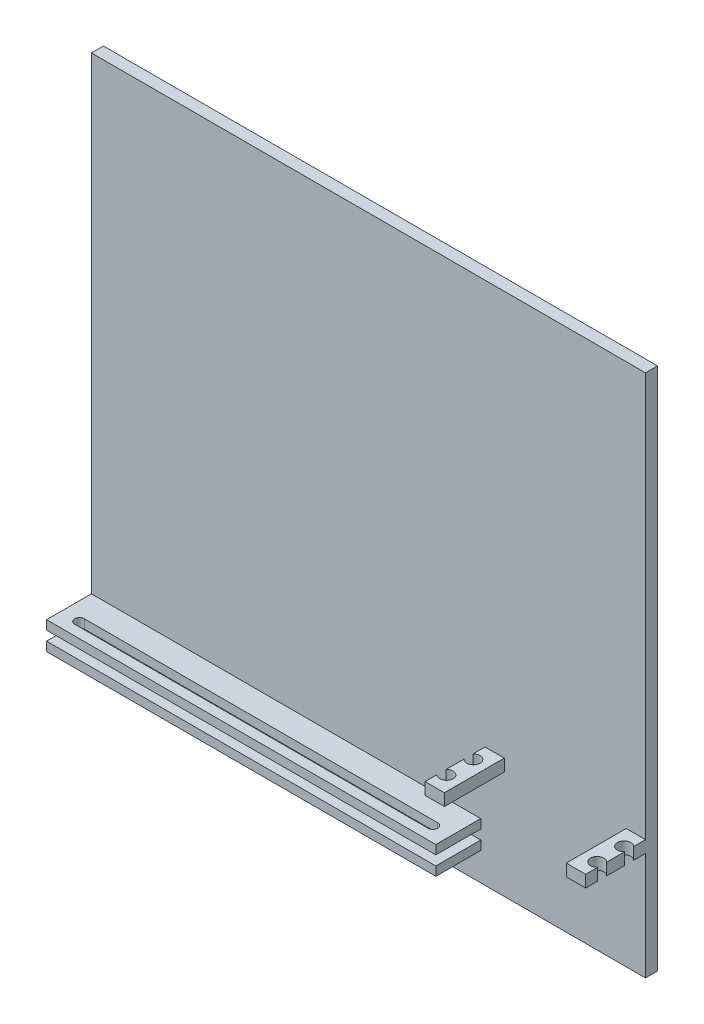
SolidWorks part; units mm, degrees
ref_plane "前基準面" through (0, 0, 0) normal (0, 0, 1) x (1, 0, 0)
ref_plane "上基準面" through (0, 0, 0) normal (0, 1, 0) x (1, 0, 0)
ref_plane "右基準面" through (0, 0, 0) normal (1, 0, 0) x (0, 0, -1)
sketch "草圖1" plane through (0, 0, 0) normal (0, 0, 1) x (1, 0, 0)
  line L1 (-102.146, 128.6132) -> (82.854, 128.6132)
  line L2 (-102.146, 128.6132) -> (-102.146, -46.3868)
  line L3 (-102.146, -46.3868) -> (82.854, -46.3868)
  line L4 (82.854, 128.6132) -> (82.854, -46.3868)
  dimension "D1" = 185
  dimension "D2" = 175
extrude "填料-伸長1" add sketch "草圖1" along normal blind 4
sketch "草圖2" plane through (0, 0, 4) normal (0, 0, 1) x (1, 0, 0)
  line L0 (76.204, -10.3868) -> (82.254, -10.3868) construction
  line L1 (76.404, -10.3868) -> (82.854, -10.3868)
  line L2 (76.404, -10.3868) -> (76.404, -6.3868)
  line L3 (76.404, -6.3868) -> (82.854, -6.3868)
  line L4 (82.854, -10.3868) -> (82.854, -6.3868)
  line L5 (76.204, 15.6132) -> (76.204, -10.3868) construction
  line L6 (82.854, -46.3868) -> (82.854, 128.6132) construction
  line L7 (29.854, -10.3868) -> (35.904, -10.3868) construction
  line L8 (35.704, -10.3868) -> (29.254, -10.3868)
  line L9 (35.704, -10.3868) -> (35.704, -6.3868)
  line L10 (35.704, -6.3868) -> (29.254, -6.3868)
  line L11 (29.254, -10.3868) -> (29.254, -6.3868)
  line L12 (35.904, -10.3868) -> (35.904, 15.6132) construction
  line L13 (29.254, -12.7868) -> (29.254, -10.9868) construction
  dimension "D1" = 0.2
  dimension "D2" = 4
  dimension "D3" = 0.2
  dimension "D4" = 4
extrude "填料-伸長2" add sketch "草圖2" along normal up to vertex (20 mm away)
sketch "草圖3" plane through (0, -10.3868, 0) normal (0, -1, 0) x (1, 0, 0)
  circle A0 centre (81.204, 18.5) radius 2.22
  circle A1 centre (81.204, 9.5) radius 2.22
  circle A2 centre (30.904, 9.5) radius 2.22
  circle A3 centre (30.904, 18.5) radius 2.22
extrude "除料-伸長1" cut sketch "草圖3" against normal up to next
sketch "草圖4" plane through (0, 0, 4) normal (0, 0, 1) x (1, 0, 0)
  line L0 (-102.146, 128.6132) -> (-102.146, -46.3868) construction
  line L1 (-102.146, -30.7868) -> (27.854, -30.7868)
  line L2 (-102.146, -30.7868) -> (-102.146, -27.7868)
  line L3 (-102.146, -27.7868) -> (27.854, -27.7868)
  line L4 (27.854, -30.7868) -> (27.854, -27.7868)
  line L5 (64.3284, -30.8868) -> (19.9992, -30.8868) construction
  line L6 (-102.146, -33.9868) -> (27.854, -33.9868)
  line L7 (-102.146, -33.9868) -> (-102.146, -36.9868)
  line L8 (-102.146, -36.9868) -> (27.854, -36.9868)
  line L9 (27.854, -33.9868) -> (27.854, -36.9868)
  dimension "D1" = 0.1
  dimension "D2" = 3
  dimension "D3" = 130
  dimension "D4" = 3.2
  dimension "D5" = 130
  dimension "D6" = 3
extrude "填料-伸長3" add sketch "草圖4" along normal blind 15
sketch "草圖5" plane through (0, -36.9868, 0) normal (0, -1, 0) x (1, 0, 0)
  line L0 (-96.146, 14) -> (21.854, 14) construction
  line L1 (-96.146, 15.6) -> (21.854, 15.6)
  line L2 (-96.146, 12.4) -> (21.854, 12.4)
  line L3 (-102.146, 19) -> (-102.146, 4) construction
  line L4 (27.854, 19) -> (27.854, 4) construction
  line L5 (-102.146, 4) -> (27.854, 4) construction
  arc A0 (-96.146, 15.6) -> (-96.146, 12.4) centre (-96.146, 14) ccw
  arc A1 (21.854, 12.4) -> (21.854, 15.6) centre (21.854, 14) ccw
  point P2 (-37.146, 14)
  dimension "D3" = 1.6
  dimension "D1" = 6
  dimension "D2" = 6
  dimension "D4" = 10
extrude "除料-伸長2" cut sketch "草圖5" against normal up to surface (9.2 mm away) up to face at (-37.146, -27.7868, 11.5)
